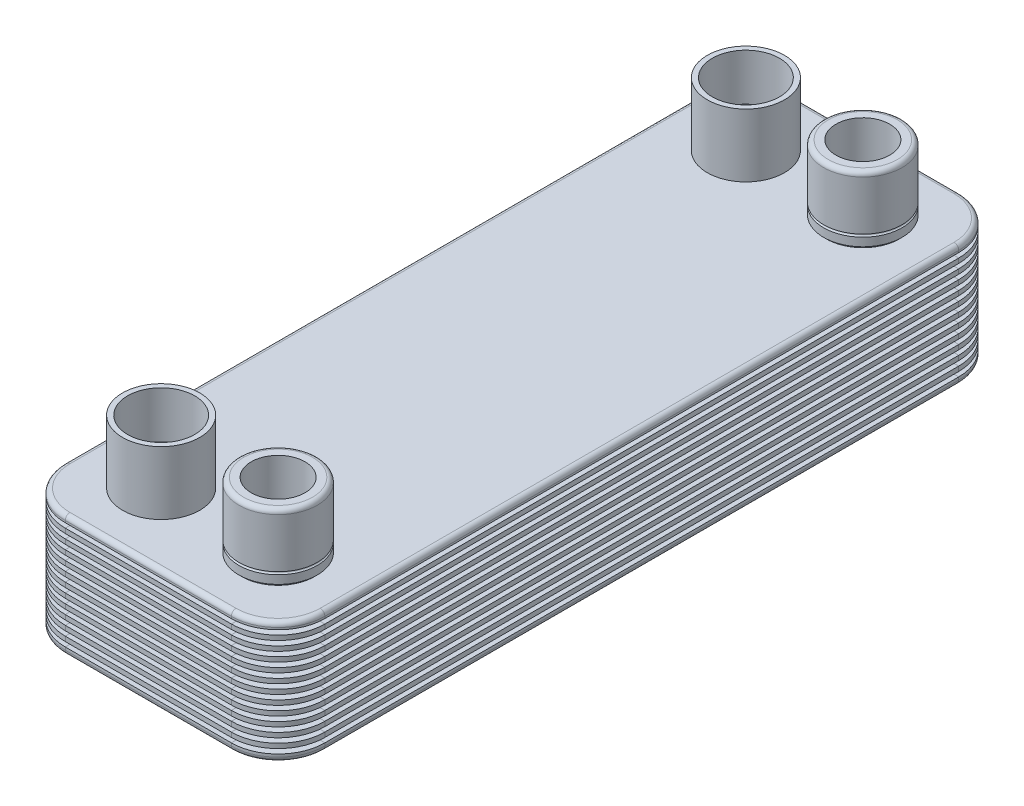
SolidWorks part; units mm, degrees
ref_plane "Front Plane" through (0, 0, 0) normal (0, 0, 1) x (1, 0, 0)
ref_plane "Top Plane" through (0, 0, 0) normal (0, 1, 0) x (1, 0, 0)
ref_plane "Right Plane" through (0, 0, 0) normal (1, 0, 0) x (0, 0, -1)
sketch "Sketch1" plane through (0, 0, 0) normal (0, 1, 0) x (1, 0, 0)
  line L1 (-35.5, -155.5) -> (35.5, -155.5)
  line L2 (-55.5, -135.5) -> (-55.5, 135.5)
  line L3 (-35.5, 155.5) -> (35.5, 155.5)
  line L4 (55.5, -135.5) -> (55.5, 135.5)
  line L5 (-55.5, -155.5) -> (55.5, 155.5) construction
  line L6 (-55.5, 155.5) -> (55.5, -155.5) construction
  arc A0 (-35.5, -155.5) -> (-55.5, -135.5) centre (-35.5, -135.5) cw
  arc A1 (35.5, -155.5) -> (55.5, -135.5) centre (35.5, -135.5) ccw
  arc A2 (35.5, 155.5) -> (55.5, 135.5) centre (35.5, 135.5) cw
  arc A3 (-55.5, 135.5) -> (-35.5, 155.5) centre (-35.5, 135.5) cw
  point P0 (0, 0)
  dimension "D3" = 20
  dimension "D1" = 311
  dimension "D2" = 111
extrude "Boss-Extrude1" add sketch "Sketch1" along normal blind 52
ref_plane "Plane2" through (0, 0, 135.5) normal (0, 0, 1) x (1, 0, 0)
sketch "Sketch2" plane through (0, 0, 135.5) normal (0, 0, 1) x (1, 0, 0)
  line L0 (-55.5, 52) -> (-55.5, 0) construction
  line L1 (-58.5, 49.1725) -> (-52.5, 49.1725)
  line L2 (-58.5, 49.1725) -> (-58.5, 47.1725)
  line L3 (-58.5, 47.1725) -> (-52.5, 47.1725)
  line L4 (-52.5, 49.1725) -> (-52.5, 47.1725)
  line L5 (-58.5, 49.1725) -> (-52.5, 47.1725) construction
  line L6 (-58.5, 47.1725) -> (-52.5, 49.1725) construction
  line L7 (-58.5, 43.1725) -> (-52.5, 43.1725)
  line L8 (-58.5, 45.1725) -> (-58.5, 43.1725)
  line L9 (-58.5, 45.1725) -> (-52.5, 45.1725)
  line L10 (-52.5, 45.1725) -> (-52.5, 43.1725)
  line L11 (-58.5, 39.1725) -> (-52.5, 39.1725)
  line L12 (-58.5, 41.1725) -> (-58.5, 39.1725)
  line L13 (-58.5, 41.1725) -> (-52.5, 41.1725)
  line L14 (-52.5, 41.1725) -> (-52.5, 39.1725)
  line L15 (-58.5, 35.1725) -> (-52.5, 35.1725)
  line L16 (-58.5, 37.1725) -> (-58.5, 35.1725)
  line L17 (-58.5, 37.1725) -> (-52.5, 37.1725)
  line L18 (-52.5, 37.1725) -> (-52.5, 35.1725)
  line L19 (-58.5, 31.1725) -> (-52.5, 31.1725)
  line L20 (-58.5, 33.1725) -> (-58.5, 31.1725)
  line L21 (-58.5, 33.1725) -> (-52.5, 33.1725)
  line L22 (-52.5, 33.1725) -> (-52.5, 31.1725)
  line L23 (-58.5, 27.1725) -> (-52.5, 27.1725)
  line L24 (-58.5, 29.1725) -> (-58.5, 27.1725)
  line L25 (-58.5, 29.1725) -> (-52.5, 29.1725)
  line L26 (-52.5, 29.1725) -> (-52.5, 27.1725)
  line L27 (-58.5, 23.1725) -> (-52.5, 23.1725)
  line L28 (-58.5, 25.1725) -> (-58.5, 23.1725)
  line L29 (-58.5, 25.1725) -> (-52.5, 25.1725)
  line L30 (-52.5, 25.1725) -> (-52.5, 23.1725)
  line L31 (-58.5, 19.1725) -> (-52.5, 19.1725)
  line L32 (-58.5, 21.1725) -> (-58.5, 19.1725)
  line L33 (-58.5, 21.1725) -> (-52.5, 21.1725)
  line L34 (-52.5, 21.1725) -> (-52.5, 19.1725)
  line L35 (-58.5, 15.1725) -> (-52.5, 15.1725)
  line L36 (-58.5, 17.1725) -> (-58.5, 15.1725)
  line L37 (-58.5, 17.1725) -> (-52.5, 17.1725)
  line L38 (-52.5, 17.1725) -> (-52.5, 15.1725)
  line L39 (-58.5, 11.1725) -> (-52.5, 11.1725)
  line L40 (-58.5, 13.1725) -> (-58.5, 11.1725)
  line L41 (-58.5, 13.1725) -> (-52.5, 13.1725)
  line L42 (-52.5, 13.1725) -> (-52.5, 11.1725)
  line L43 (-58.5, 7.1725) -> (-52.5, 7.1725)
  line L44 (-58.5, 9.1725) -> (-58.5, 7.1725)
  line L45 (-58.5, 9.1725) -> (-52.5, 9.1725)
  line L46 (-52.5, 9.1725) -> (-52.5, 7.1725)
  line L47 (-58.5, 3.1725) -> (-52.5, 3.1725)
  line L48 (-58.5, 5.1725) -> (-58.5, 3.1725)
  line L49 (-58.5, 5.1725) -> (-52.5, 5.1725)
  line L50 (-52.5, 5.1725) -> (-52.5, 3.1725)
  point P0 (-55.5, 48.1725)
  dimension "D1" = 2
  dimension "D2" = 6
  dimension "D3" = 12
ref_plane "Plane1" through (0, 48.1725, 0) normal (0, 1, 0) x (1, 0, 0)
sketch "Sketch3" plane through (0, 48.1725, 0) normal (0, 1, 0) x (1, 0, 0)
  line L4 (-35.5, -155.5) -> (35.5, -155.5)
  line L5 (55.5, -135.5) -> (55.5, 135.5)
  line L6 (35.5, 155.5) -> (-35.5, 155.5)
  line L7 (-55.5, 135.5) -> (-55.5, -135.5)
  line L8 (-35.5, -155.5) -> (35.5, -155.5)
  line L9 (55.5, -135.5) -> (55.5, 135.5)
  line L10 (35.5, 155.5) -> (-35.5, 155.5)
  line L11 (-55.5, 135.5) -> (-55.5, -135.5)
  arc A4 (-55.5, -135.5) -> (-35.5, -155.5) centre (-35.5, -135.5) ccw
  arc A5 (35.5, -155.5) -> (55.5, -135.5) centre (35.5, -135.5) ccw
  arc A6 (55.5, 135.5) -> (35.5, 155.5) centre (35.5, 135.5) ccw
  arc A7 (-35.5, 155.5) -> (-55.5, 135.5) centre (-35.5, 135.5) ccw
  arc A8 (-55.5, -135.5) -> (-35.5, -155.5) centre (-35.5, -135.5) ccw
  arc A9 (35.5, -155.5) -> (55.5, -135.5) centre (35.5, -135.5) ccw
  arc A10 (55.5, 135.5) -> (35.5, 155.5) centre (35.5, 135.5) ccw
  arc A11 (-35.5, 155.5) -> (-55.5, 135.5) centre (-35.5, 135.5) ccw
  dimension "D1" = 0
sweep "Cut-Sweep1" cut profiles "Sketch2" path "Sketch3"
fillet "Fillet1" radius 2 16 edges at (0, 0, 155.5) (49.6421, 0, 149.6421) (55.5, 0, 0) (49.6421, 0, -149.6421) (0, 0, -155.5) (-49.6421, 0, -149.6421) (-55.5, 0, 0) (-49.6421, 0, 149.6421) (-55.5, 52, 0) (-49.6421, 52, -149.6421) (0, 52, -155.5) (49.6421, 52, -149.6421) (55.5, 52, 0) (49.6421, 52, 149.6421) (0, 52, 155.5) (-49.6421, 52, 149.6421)
sketch "Sketch4" plane through (0, 52, 0) normal (0, 1, 0) x (1, 0, 0)
  line L0 (0, 153.5) -> (0, -153.5) construction
  line L1 (35.5, 153.5) -> (-35.5, 153.5) construction
  line L2 (-35.5, -153.5) -> (35.5, -153.5) construction
  line L3 (0, 0) -> (147.3626, 0) construction
  point P6 (-25, 125)
  point P9 (25, 125)
  dimension "D1" = 50
  dimension "D2" = 250
ref_plane "Plane3" through (0, 0, -125) normal (0, 0, -1) x (-1, 0, 0)
sketch "Sketch5" plane through (0, 0, -125) normal (0, 0, -1) x (-1, 0, 0)
  line L0 (8.5, 52) -> (8.5, 79)
  line L1 (0, 52) -> (-147.3626, 52) construction
  line L2 (8.5, 79) -> (10.65, 79)
  line L5 (10.65, 79) -> (10.65, 59)
  line L6 (10.65, 59) -> (13.5, 59)
  line L7 (13.5, 59) -> (13.5, 52)
  line L8 (13.5, 52) -> (8.5, 52)
  line L9 (25, 52) -> (25, 72.8377) construction
  dimension "D1" = 33
  dimension "D2" = 20
  dimension "D3" = 28.7
  dimension "D4" = 23
  dimension "D6" = 27
revolve "Revolve1" add sketch "Sketch5" angle 360 about L9
sketch "Sketch6" plane through (0, 0, -125) normal (0, 0, -1) x (-1, 0, 0)
  line L0 (-25, 52) -> (-25, 79.0984) construction
  line L1 (-36.5, 52) -> (-36.5, 81)
  line L2 (0, 52) -> (-147.3626, 52) construction
  line L3 (-36.5, 81) -> (-39.75, 81)
  line L4 (-41.75, 79) -> (-41.75, 57.8555)
  line L5 (-41.75, 56.7443) -> (-41.75, 53.1724)
  line L6 (-41.75, 53.1724) -> (-40.5776, 53.1724)
  line L7 (-40.5776, 53.1724) -> (-40.5776, 52)
  line L8 (-40.5776, 52) -> (-36.5, 52)
  line L9 (-41.75, 61) -> (-39.2611, 63.4889) construction
  line L10 (-39.2611, 63.4889) -> (-39.2611, 81) construction
  arc A0 (-41.75, 57.8555) -> (-41.75, 56.7443) centre (-41.75, 57.2999) cw
  arc A1 (-39.75, 81) -> (-41.75, 79) centre (-39.75, 79) ccw
  point P22 (-41.75, 81)
  dimension "D5" = 2
  dimension "D1" = 33.5
  dimension "D2" = 23
  dimension "D3" = 20
  dimension "D4" = 29
revolve "Revolve2" add sketch "Sketch6" angle 360 about L0
mirror "Mirror1" about plane through (0, 0, 0) normal (0, 0, 1) of bodies 104 103
